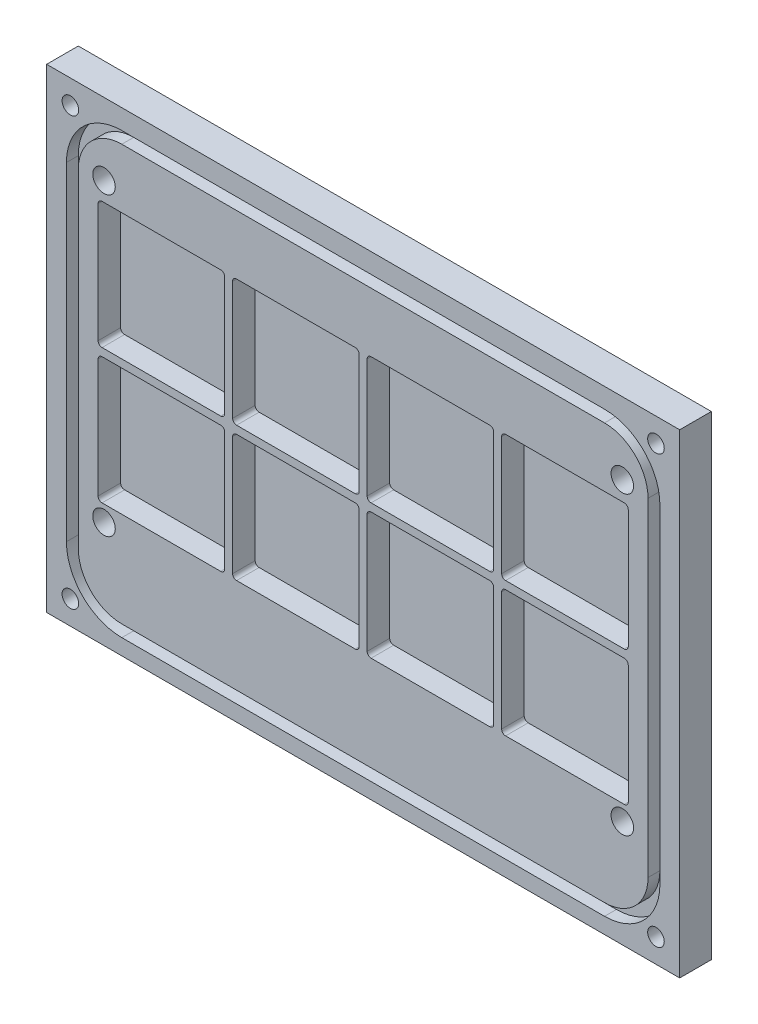
SolidWorks part; units mm, degrees
ref_plane "Plan de face" through (0, 0, 0) normal (0, 0, 1) x (1, 0, 0)
ref_plane "Plan de dessus" through (0, 0, 0) normal (0, 1, 0) x (1, 0, 0)
ref_plane "Plan de droite" through (0, 0, 0) normal (1, 0, 0) x (0, 0, -1)
sketch "Esquisse1" plane through (0, 0, 0) normal (0, 0, 1) x (1, 0, 0)
  line L1 (-87.2277, 54.0323) -> (72.7723, 54.0323)
  line L2 (-87.2277, 54.0323) -> (-87.2277, -65.9677)
  line L3 (-87.2277, -65.9677) -> (72.7723, -65.9677)
  line L4 (72.7723, 54.0323) -> (72.7723, -65.9677)
  dimension "D1" = 120
  dimension "D2" = 160
extrude "Boss.-Extru.1" add sketch "Esquisse1" along normal blind 8
sketch "Esquisse2" plane through (0, 0, 8) normal (0, 0, 1) x (1, 0, 0)
  line L0 (-40.2277, 31.0323) -> (-8.2277, 31.0323)
  line L1 (-74.2277, 31.0323) -> (-42.2277, 31.0323)
  line L2 (-74.2277, 31.0323) -> (-74.2277, -0.9677)
  line L3 (-74.2277, -0.9677) -> (-42.2277, -0.9677)
  line L4 (-42.2277, 31.0323) -> (-42.2277, -0.9677)
  line L5 (-8.2277, 31.0323) -> (-8.2277, -0.9677)
  line L6 (-40.2277, -0.9677) -> (-8.2277, -0.9677)
  line L7 (-40.2277, 31.0323) -> (-40.2277, -0.9677)
  line L8 (-6.2277, 31.0323) -> (25.7723, 31.0323)
  line L9 (25.7723, 31.0323) -> (25.7723, -0.9677)
  line L10 (-6.2277, -0.9677) -> (25.7723, -0.9677)
  line L11 (-6.2277, 31.0323) -> (-6.2277, -0.9677)
  line L12 (27.7723, 31.0323) -> (59.7723, 31.0323)
  line L13 (59.7723, 31.0323) -> (59.7723, -0.9677)
  line L14 (27.7723, -0.9677) -> (59.7723, -0.9677)
  line L15 (27.7723, 31.0323) -> (27.7723, -0.9677)
  line L16 (-40.2277, -2.9677) -> (-8.2277, -2.9677)
  line L17 (-8.2277, -2.9677) -> (-8.2277, -34.9677)
  line L18 (-40.2277, -34.9677) -> (-8.2277, -34.9677)
  line L19 (-40.2277, -2.9677) -> (-40.2277, -34.9677)
  line L20 (-6.2277, -2.9677) -> (25.7723, -2.9677)
  line L21 (25.7723, -2.9677) -> (25.7723, -34.9677)
  line L22 (-6.2277, -34.9677) -> (25.7723, -34.9677)
  line L23 (-6.2277, -2.9677) -> (-6.2277, -34.9677)
  line L24 (27.7723, -2.9677) -> (59.7723, -2.9677)
  line L25 (59.7723, -2.9677) -> (59.7723, -34.9677)
  line L26 (27.7723, -34.9677) -> (59.7723, -34.9677)
  line L27 (27.7723, -2.9677) -> (27.7723, -34.9677)
  line L28 (-74.2277, -2.9677) -> (-42.2277, -2.9677)
  line L29 (-42.2277, -2.9677) -> (-42.2277, -34.9677)
  line L30 (-74.2277, -34.9677) -> (-42.2277, -34.9677)
  line L31 (-74.2277, -2.9677) -> (-74.2277, -34.9677)
  line L32 (72.7723, 54.0323) -> (-87.2277, 54.0323) construction
  line L34 (-87.2277, 54.0323) -> (-87.2277, -65.9677) construction
  dimension "D1" = 32
  dimension "D2" = 32
  dimension "D5" = 23
  dimension "D6" = 13
  dimension "D7" = 2
  dimension "D8" = 2
  dimension "D3" = 4
  dimension "D4" = 2
extrude "Enlèv. mat.-Extru.1" cut sketch "Esquisse2" against normal blind 5.7
sketch "Esquisse3" plane through (0, 0, 8) normal (0, 0, 1) x (1, 0, 0)
  line L1 (-68.2277, 49.0323) -> (53.7723, 49.0323)
  line L2 (-82.2277, 35.0323) -> (-82.2277, -47.9677)
  line L3 (-68.2277, -61.9677) -> (53.7723, -61.9677)
  line L4 (67.7723, 35.0323) -> (67.7723, -47.9677)
  line L8 (-79.2277, 35.0323) -> (-79.2277, -47.9677)
  line L9 (-68.2277, -58.9677) -> (53.7723, -58.9677)
  line L10 (64.7723, 35.0323) -> (64.7723, -47.9677)
  line L11 (-68.2277, 46.0323) -> (53.7723, 46.0323)
  line L12 (-87.2277, -65.9677) -> (72.7723, -65.9677) construction
  line L13 (72.7723, 54.0323) -> (-87.2277, 54.0323) construction
  line L14 (72.7723, -65.9677) -> (72.7723, 54.0323) construction
  line L15 (-87.2277, 54.0323) -> (-87.2277, -65.9677) construction
  arc A0 (53.7723, 49.0323) -> (67.7723, 35.0323) centre (53.7723, 35.0323) cw
  arc A1 (53.7723, -61.9677) -> (67.7723, -47.9677) centre (53.7723, -47.9677) ccw
  arc A2 (-82.2277, -47.9677) -> (-68.2277, -61.9677) centre (-68.2277, -47.9677) ccw
  arc A3 (-68.2277, 49.0323) -> (-82.2277, 35.0323) centre (-68.2277, 35.0323) ccw
  arc A4 (-68.2277, 46.0323) -> (-79.2277, 35.0323) centre (-68.2277, 35.0323) ccw
  arc A5 (-79.2277, -47.9677) -> (-68.2277, -58.9677) centre (-68.2277, -47.9677) ccw
  arc A6 (53.7723, -58.9677) -> (64.7723, -47.9677) centre (53.7723, -47.9677) ccw
  arc A7 (53.7723, 46.0323) -> (64.7723, 35.0323) centre (53.7723, 35.0323) cw
  dimension "D5" = 14
  dimension "D1" = 4
  dimension "D2" = 5
  dimension "D3" = 5
  dimension "D4" = 5
  dimension "D6" = 3
extrude "Enlèv. mat.-Extru.2" cut sketch "Esquisse3" against normal blind 3
ref_plane "Plan1" through (-87.2277, 54.0323, 8) normal (-1, 0, 0) x (0, 0, 1)
sketch "Esquisse4" plane through (-87.2277, 54.0323, 8) normal (-1, 0, 0) x (0, 0, 1)
hole_wizard "Trou pour taraudage pour trou taraudé M51" positions "Esquisse5" profile "Esquisse6" hole size "M5" standard "ISO"
sketch "Esquisse5" plane through (0, 0, 8) normal (0, 0, 1) x (1, 0, 0)
  line L0 (-87.2277, 54.0323) -> (-87.2277, -65.9677) construction
  line L1 (-87.2277, -65.9677) -> (72.7723, -65.9677) construction
  line L2 (72.7723, 54.0323) -> (-87.2277, 54.0323) construction
  line L7 (72.7723, -65.9677) -> (72.7723, 54.0323) construction
  point P0 (-81.2277, -59.9677)
  point P2 (-81.2277, 48.0323)
  point P4 (66.7723, 48.0323)
  point P6 (66.7723, -59.9677)
  dimension "D1" = 6
  dimension "D2" = 6
  dimension "D3" = 6
  dimension "D4" = 6
  dimension "D5" = 6
  dimension "D6" = 6
  dimension "D7" = 6
  dimension "D8" = 6
sketch "Esquisse6" plane through (-81.2277, -59.9677, 8) normal (1, 0, 0) x (0, -1, 0)
  line L0 (0, 0) -> (0, 9.2618)
  line L1 (0, 9.2618) -> (2.1, 8)
  line L2 (2.1, 8) -> (2.1, 0)
  line L5 (2.1, 0) -> (0, 0)
  line L10 (0, 9.2618) -> (-2.1, 8) construction
  line L11 (0, -6.35) -> (0, 107.95) construction
  dimension "Diamètre du perçage" = 4.2
  dimension "Profondeur du perçage" = 8
  dimension "Angle de pointe" = 118
fillet "Congé1" radius 1 32 edges at (-8.2277, 31.0323, 5.15) (25.7723, 31.0323, 5.15) (59.7723, 31.0323, 5.15) (59.7723, -2.9677, 5.15) (25.7723, -2.9677, 5.15) (-8.2277, -2.9677, 5.15) (-42.2277, -2.9677, 5.15) (-74.2277, -2.9677, 5.15) (-40.2277, -2.9677, 5.15) (-6.2277, -2.9677, 5.15) (27.7723, -2.9677, 5.15) (27.7723, 31.0323, 5.15) (-6.2277, 31.0323, 5.15) (-40.2277, 31.0323, 5.15) (-40.2277, -0.9677, 5.15) (-6.2277, -0.9677, 5.15) (27.7723, -0.9677, 5.15) (27.7723, -34.9677, 5.15) (-6.2277, -34.9677, 5.15) (-40.2277, -34.9677, 5.15) (-74.2277, -34.9677, 5.15) (-42.2277, -34.9677, 5.15) (-8.2277, -34.9677, 5.15) (25.7723, -34.9677, 5.15) (59.7723, -34.9677, 5.15) (59.7723, -0.9677, 5.15) (25.7723, -0.9677, 5.15) (-8.2277, -0.9677, 5.15) (-42.2277, -0.9677, 5.15) (-74.2277, -0.9677, 5.15) (-42.2277, 31.0323, 5.15) (-74.2277, 31.0323, 5.15)
sketch "Esquisse7" plane through (0, 0, 8) normal (0, 0, 1) x (1, 0, 0)
  line L0 (-87.2277, 54.0323) -> (-87.2277, -65.9677) construction
  line L2 (72.7723, 54.0323) -> (-87.2277, 54.0323) construction
  circle A0 centre (-72.7277, 35.8323) radius 2.845
  circle A2 centre (-72.7277, -38.9677) radius 2.845
  circle A3 centre (-72.7277, -38.9677) radius 1.25 construction
  circle A4 centre (58.2723, -38.9677) radius 2.845
  circle A5 centre (58.2723, 35.8323) radius 2.845
  circle A6 centre (58.2723, 35.8323) radius 1.25 construction
  dimension "D1" = 14.5
  dimension "D3" = 0
  dimension "D4" = 5.69
  dimension "D5" = 0
  dimension "D6" = 5.69
  dimension "D7" = 5.69
  dimension "D2" = 18.2
  dimension "D8" = 0
extrude "Enlèv. mat.-Extru.3" cut sketch "Esquisse7" against normal blind 6
